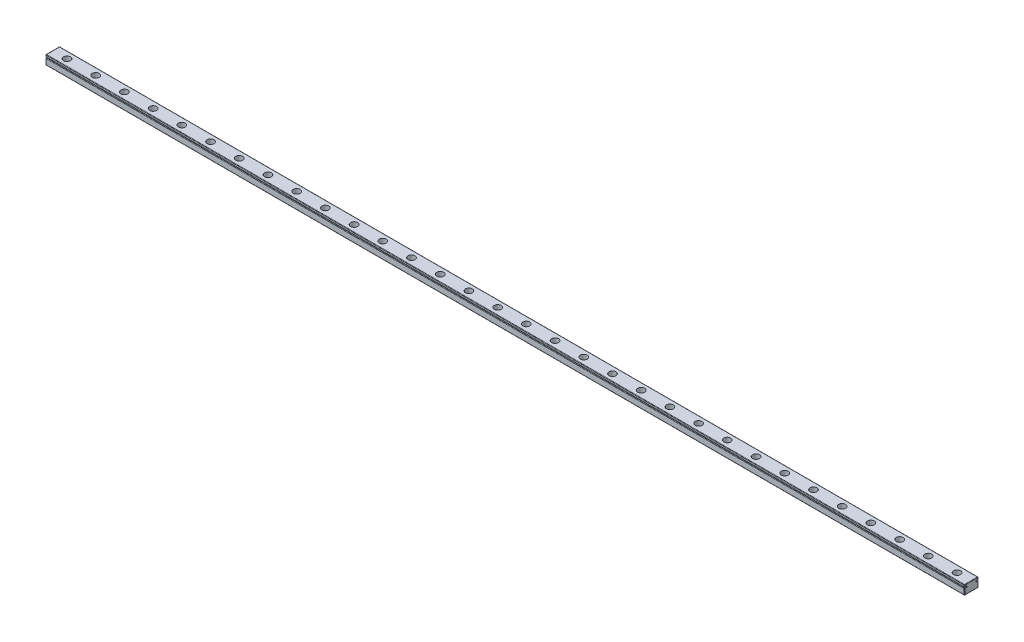
SolidWorks part; units mm, degrees
ref_plane "Front Plane" through (0, 0, 0) normal (0, 0, 1) x (1, 0, 0)
ref_plane "Top Plane" through (0, 0, 0) normal (0, 1, 0) x (1, 0, 0)
ref_plane "Right Plane" through (0, 0, 0) normal (1, 0, 0) x (0, 0, -1)
sketch "Sketch1" plane through (0, 0, 0) normal (1, 0, 0) x (0, 0, -1)
  line L1 (6, -4) -> (-6, -4)
  line L2 (6, -4) -> (6, 4)
  line L3 (6, 4) -> (-6, 4)
  line L4 (-6, -4) -> (-6, 4)
  line L5 (6, -4) -> (-6, 4) construction
  line L6 (6, 4) -> (-6, -4) construction
  point P0 (0, 0)
  dimension "D1" = 8
  dimension "D2" = 12
extrude "Boss-Extrude1" add sketch "Sketch1" along normal blind 800
sketch "Sketch2" plane through (0, 4, 0) normal (0, 1, 0) x (1, 0, 0)
  line L0 (400, 6) -> (400, -6) construction
  line L1 (800, 6) -> (0, 6) construction
  line L2 (800, -6) -> (0, -6) construction
  line L3 (400, 0) -> (412.5, 0) construction
  circle A0 centre (412.5, 0) radius 3
  circle A1 centre (437.5, 0) radius 3
  circle A2 centre (462.5, 0) radius 3
  circle A3 centre (487.5, 0) radius 3
  circle A4 centre (512.5, 0) radius 3
  circle A5 centre (537.5, 0) radius 3
  circle A6 centre (562.5, 0) radius 3
  circle A7 centre (587.5, 0) radius 3
  circle A8 centre (612.5, 0) radius 3
  circle A9 centre (637.5, 0) radius 3
  circle A10 centre (662.5, 0) radius 3
  circle A11 centre (687.5, 0) radius 3
  circle A12 centre (712.5, 0) radius 3
  circle A13 centre (737.5, 0) radius 3
  circle A14 centre (762.5, 0) radius 3
  circle A15 centre (787.5, 0) radius 3
  circle A16 centre (387.5, 0) radius 3
  circle A17 centre (362.5, 0) radius 3
  circle A18 centre (337.5, 0) radius 3
  circle A19 centre (312.5, 0) radius 3
  circle A20 centre (287.5, 0) radius 3
  circle A21 centre (262.5, 0) radius 3
  circle A22 centre (237.5, 0) radius 3
  circle A23 centre (212.5, 0) radius 3
  circle A24 centre (187.5, 0) radius 3
  circle A25 centre (162.5, 0) radius 3
  circle A26 centre (137.5, 0) radius 3
  circle A27 centre (112.5, 0) radius 3
  circle A28 centre (87.5, 0) radius 3
  circle A29 centre (62.5, 0) radius 3
  circle A30 centre (37.5, 0) radius 3
  circle A31 centre (12.5, 0) radius 3
  dimension "D1" = 12.5
  dimension "D2" = 6
  dimension "D3" = 16
  dimension "D4" = 17
extrude "Cut-Extrude1" cut sketch "Sketch2" against normal blind 4.5
sketch "Sketch3" plane through (0, -0.5, 0) normal (0, 1, 0) x (1, 0, 0)
  circle A0 centre (12.5, 0) radius 1.75
  circle A1 centre (37.5, 0) radius 1.75
  circle A2 centre (62.5, 0) radius 1.75
  circle A3 centre (87.5, 0) radius 1.75
  circle A4 centre (112.5, 0) radius 1.75
  circle A5 centre (137.5, 0) radius 1.75
  circle A6 centre (162.5, 0) radius 1.75
  circle A7 centre (187.5, 0) radius 1.75
  circle A8 centre (212.5, 0) radius 1.75
  circle A9 centre (237.5, 0) radius 1.75
  circle A10 centre (262.5, 0) radius 1.75
  circle A11 centre (287.5, 0) radius 1.75
  circle A12 centre (312.5, 0) radius 1.75
  circle A13 centre (337.5, 0) radius 1.75
  circle A14 centre (362.5, 0) radius 1.75
  circle A15 centre (387.5, 0) radius 1.75
  circle A16 centre (412.5, 0) radius 1.75
  circle A17 centre (437.5, 0) radius 1.75
  circle A18 centre (462.5, 0) radius 1.75
  circle A19 centre (487.5, 0) radius 1.75
  circle A20 centre (512.5, 0) radius 1.75
  circle A21 centre (537.5, 0) radius 1.75
  circle A22 centre (562.5, 0) radius 1.75
  circle A23 centre (587.5, 0) radius 1.75
  circle A24 centre (612.5, 0) radius 1.75
  circle A25 centre (637.5, 0) radius 1.75
  circle A26 centre (662.5, 0) radius 1.75
  circle A27 centre (687.5, 0) radius 1.75
  circle A28 centre (712.5, 0) radius 1.75
  circle A29 centre (737.5, 0) radius 1.75
  circle A30 centre (762.5, 0) radius 1.75
  circle A31 centre (787.5, 0) radius 1.75
  dimension "D1" = 3.5
  dimension "D2" = 32
extrude "Cut-Extrude2" cut sketch "Sketch3" against normal up to next (3.5 mm away)
sketch "Sketch4" plane through (0, 0, 0) normal (-1, 0, 0) x (0, 0, 1)
  line L0 (-6, 2) -> (-4.25, 2)
  line L1 (-6, -4) -> (-6, 4) construction
  line L2 (-4.25, 2) -> (-4.25, 1.5)
  line L3 (-4.25, 1.5) -> (-6, 1.5)
  line L4 (-6, 1.5) -> (-6, 2)
  line L5 (0, 0) -> (0, -1.3388) construction
  line L6 (6, 1.5) -> (6, 2)
  line L7 (4.25, 1.5) -> (6, 1.5)
  line L8 (4.25, 2) -> (4.25, 1.5)
  line L9 (6, 2) -> (4.25, 2)
  line L10 (-6, 4) -> (6, 4) construction
  dimension "D1" = 2
  dimension "D2" = 0.5
  dimension "D3" = 1.75
extrude "Cut-Extrude3" cut sketch "Sketch4" against normal up to next
fillet "Fillet2" radius 0.4 32 edges at (800, 1.75, 4.25) (800, 2, 5.125) (800, 4, 0) (800, 2, -5.125) (800, 1.75, -4.25) (800, 1.5, -5.125) (800, -4, 0) (800, 1.5, 5.125) (400, -4, -6) (800, -1.25, -6) (400, 1.5, -6) (400, 4, -6) (400, 2, -6) (800, 3, -6) (0, -4, 0) (0, -1.25, -6) (0, 1.5, -5.125) (0, 1.75, -4.25) (0, 2, -5.125) (0, 3, -6) (0, 4, 0) (0, 2, 5.125) (0, 1.75, 4.25) (0, 1.5, 5.125) (400, 4, 6) (800, 3, 6) (400, 2, 6) (0, 3, 6) (400, -4, 6) (0, -1.25, 6) (400, 1.5, 6) (800, -1.25, 6)
